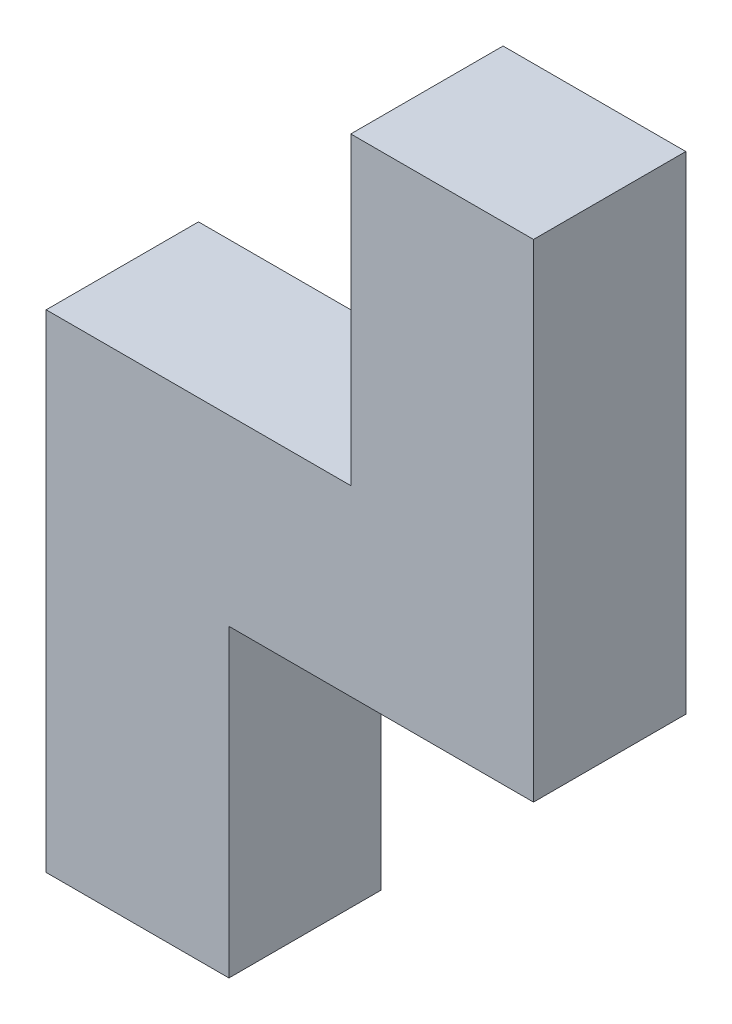
SolidWorks part; units mm, degrees
ref_plane "前基準面" through (0, 0, 0) normal (0, 0, 1) x (1, 0, 0)
ref_plane "上基準面" through (0, 0, 0) normal (0, 1, 0) x (1, 0, 0)
ref_plane "右基準面" through (0, 0, 0) normal (1, 0, 0) x (0, 0, -1)
sketch "草圖1" plane through (0, 0, 0) normal (0, 0, 1) x (1, 0, 0)
  line L0 (0, 0) -> (12, 0)
  line L1 (12, 0) -> (12, 20)
  line L2 (12, 20) -> (32, 20)
  line L3 (32, 20) -> (32, 52)
  line L4 (32, 52) -> (20, 52)
  line L5 (20, 52) -> (20, 32)
  line L6 (20, 32) -> (0, 32)
  line L7 (0, 32) -> (0, 0)
  dimension "D1" = 12
  dimension "D2" = 12
  dimension "D3" = 12
  dimension "D4" = 32
  dimension "D5" = 32
  dimension "D6" = 20
extrude "填料-伸長1" add sketch "草圖1" against normal blind 10
